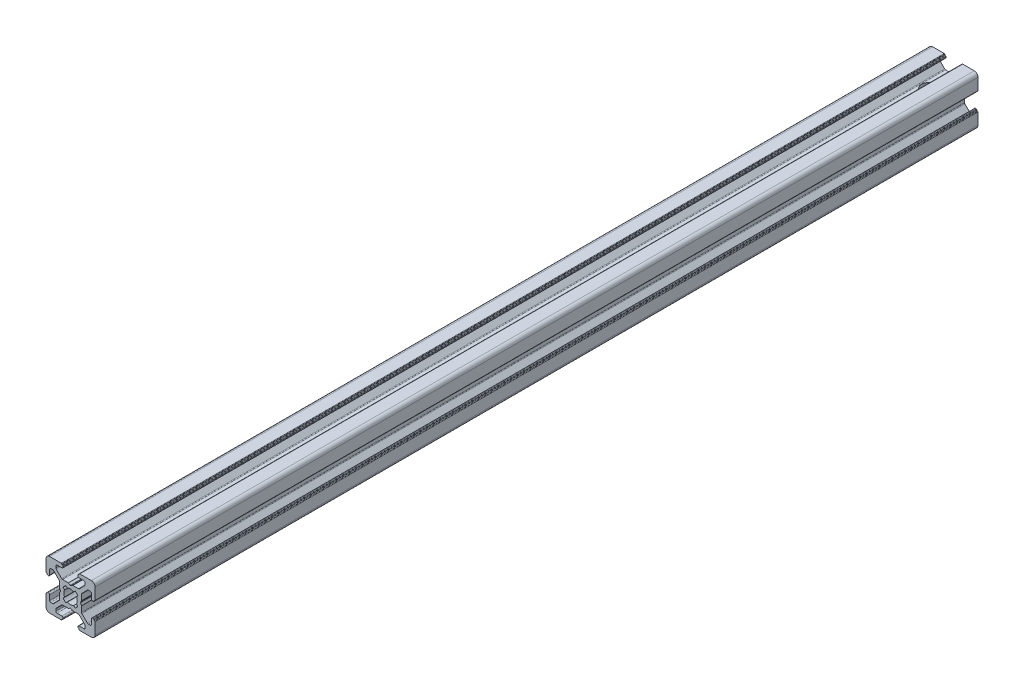
SolidWorks part; units mm, degrees
ref_plane "Ön Düzlem" through (0, 0, 0) normal (0, 0, 1) x (1, 0, 0)
ref_plane "Üst Düzlem" through (0, 0, 0) normal (0, 1, 0) x (1, 0, 0)
ref_plane "Sağ Düzlem" through (0, 0, 0) normal (1, 0, 0) x (0, 0, -1)
sketch "Çizim1" plane through (0, 0, 0) normal (0, 0, 1) x (1, 0, 0)
  line L0 (-2.9922, 1.9099) -> (-2.4453, 1.2582)
  line L1 (-2.4453, -1.2582) -> (-2.9922, -1.9099)
  line L2 (-1.9139, -2.9896) -> (-1.2582, -2.4453)
  line L3 (1.2582, -2.4453) -> (1.9139, -2.9896)
  line L4 (2.9922, -1.9099) -> (2.4453, -1.2582)
  line L5 (2.4453, 1.2582) -> (2.9922, 1.9099)
  line L6 (1.9139, 2.9896) -> (1.2582, 2.4453)
  line L7 (-1.2582, 2.4453) -> (-1.9139, 2.9896)
  line L8 (-3.75, 10) -> (-8.5, 10)
  line L9 (-3.55, 9.7) -> (-3.55, 9.8)
  line L10 (-3.2, 9.5) -> (-3.35, 9.5)
  line L11 (-3, 9) -> (-3, 9.3)
  line L12 (-5.5, 8.5) -> (-3.5, 8.5)
  line L13 (-6, 7.2678) -> (-6, 8)
  line L14 (-3.5858, 4.6464) -> (-5.8536, 6.9142)
  line L15 (-0.9536, 4.5) -> (-3.2322, 4.5)
  line L16 (-0.1, 4.0381) -> (-0.8536, 4.4732)
  line L17 (0.8536, 4.4732) -> (0.1, 4.0381)
  line L18 (3.2322, 4.5) -> (0.9536, 4.5)
  line L19 (5.8536, 6.9142) -> (3.5858, 4.6464)
  line L20 (6, 8) -> (6, 7.2678)
  line L21 (3.5, 8.5) -> (5.5, 8.5)
  line L22 (3, 9.3) -> (3, 9)
  line L23 (3.35, 9.5) -> (3.2, 9.5)
  line L24 (3.55, 9.8) -> (3.55, 9.7)
  line L25 (8.5, 10) -> (3.75, 10)
  line L26 (10, 3.75) -> (10, 8.5)
  line L27 (9.7, 3.55) -> (9.8, 3.55)
  line L28 (9.5, 3.2) -> (9.5, 3.35)
  line L29 (9, 3) -> (9.3, 3)
  line L30 (8.5, 5.5) -> (8.5, 3.5)
  line L31 (7.2678, 6) -> (8, 6)
  line L32 (4.6464, 3.5858) -> (6.9142, 5.8536)
  line L33 (4.5, 0.9536) -> (4.5, 3.2322)
  line L34 (4.0381, 0.1) -> (4.4732, 0.8536)
  line L35 (4.4732, -0.8536) -> (4.0381, -0.1)
  line L36 (4.5, -3.2322) -> (4.5, -0.9536)
  line L37 (6.9142, -5.8536) -> (4.6464, -3.5858)
  line L38 (8, -6) -> (7.2678, -6)
  line L39 (8.5, -3.5) -> (8.5, -5.5)
  line L40 (9.3, -3) -> (9, -3)
  line L41 (9.5, -3.35) -> (9.5, -3.2)
  line L42 (9.8, -3.55) -> (9.7, -3.55)
  line L43 (10, -8.5) -> (10, -3.75)
  line L44 (3.75, -10) -> (8.5, -10)
  line L45 (3.55, -9.7) -> (3.55, -9.8)
  line L46 (3.2, -9.5) -> (3.35, -9.5)
  line L47 (3, -9) -> (3, -9.3)
  line L48 (5.5, -8.5) -> (3.5, -8.5)
  line L49 (6, -7.2678) -> (6, -8)
  line L50 (3.5858, -4.6464) -> (5.8536, -6.9142)
  line L51 (0.9536, -4.5) -> (3.2322, -4.5)
  line L52 (0.1, -4.0381) -> (0.8536, -4.4732)
  line L53 (-0.8536, -4.4732) -> (-0.1, -4.0381)
  line L54 (-3.2322, -4.5) -> (-0.9536, -4.5)
  line L55 (-5.8536, -6.9142) -> (-3.5858, -4.6464)
  line L56 (-6, -8) -> (-6, -7.2678)
  line L57 (-3.5, -8.5) -> (-5.5, -8.5)
  line L58 (-3, -9.3) -> (-3, -9)
  line L59 (-3.35, -9.5) -> (-3.2, -9.5)
  line L60 (-3.55, -9.8) -> (-3.55, -9.7)
  line L61 (-8.5, -10) -> (-3.75, -10)
  line L62 (-10, -3.75) -> (-10, -8.5)
  line L63 (-9.7, -3.55) -> (-9.8, -3.55)
  line L64 (-9.5, -3.2) -> (-9.5, -3.35)
  line L65 (-9, -3) -> (-9.3, -3)
  line L66 (-8.5, -5.5) -> (-8.5, -3.5)
  line L67 (-7.2678, -6) -> (-8, -6)
  line L68 (-4.6464, -3.5858) -> (-6.9142, -5.8536)
  line L69 (-4.5, -0.9536) -> (-4.5, -3.2322)
  line L70 (-4.0381, -0.1) -> (-4.4732, -0.8536)
  line L71 (-4.4732, 0.8536) -> (-4.0381, 0.1)
  line L72 (-4.5, 3.2322) -> (-4.5, 0.9536)
  line L73 (-6.9142, 5.8536) -> (-4.6464, 3.5858)
  line L74 (-8, 6) -> (-7.2678, 6)
  line L75 (-8.5, 3.5) -> (-8.5, 5.5)
  line L76 (-9.3, 3) -> (-9, 3)
  line L77 (-9.5, 3.35) -> (-9.5, 3.2)
  line L78 (-9.8, 3.55) -> (-9.7, 3.55)
  line L79 (-10, 8.5) -> (-10, 3.75)
  arc A0 (-2.4453, 1.2582) -> (-2.4453, -1.2582) centre (0, 0) ccw
  arc A1 (-2.9922, -1.9099) -> (-1.9139, -2.9896) centre (0, 0) ccw
  arc A2 (-1.2582, -2.4453) -> (1.2582, -2.4453) centre (0, 0) ccw
  arc A3 (1.9139, -2.9896) -> (2.9922, -1.9099) centre (0, 0) ccw
  arc A4 (2.4453, -1.2582) -> (2.4453, 1.2582) centre (0, 0) ccw
  arc A5 (2.9922, 1.9099) -> (1.9139, 2.9896) centre (0, 0) ccw
  arc A6 (1.2582, 2.4453) -> (-1.2582, 2.4453) centre (0, 0) ccw
  arc A7 (-1.9139, 2.9896) -> (-2.9922, 1.9099) centre (0, 0) ccw
  arc A8 (-3.55, 9.8) -> (-3.75, 10) centre (-3.75, 9.8) ccw
  arc A9 (-3.55, 9.7) -> (-3.35, 9.5) centre (-3.35, 9.7) ccw
  arc A10 (-3, 9.3) -> (-3.2, 9.5) centre (-3.2, 9.3) ccw
  arc A11 (-3.5, 8.5) -> (-3, 9) centre (-3.5, 9) ccw
  arc A12 (-5.5, 8.5) -> (-6, 8) centre (-5.5, 8) ccw
  arc A13 (-6, 7.2678) -> (-5.8536, 6.9142) centre (-5.5, 7.2678) ccw
  arc A14 (-3.5858, 4.6464) -> (-3.2322, 4.5) centre (-3.2322, 5) ccw
  arc A15 (-0.8536, 4.4732) -> (-0.9536, 4.5) centre (-0.9536, 4.3) ccw
  arc A16 (-0.1, 4.0381) -> (0.1, 4.0381) centre (0, 4.2113) ccw
  arc A17 (0.9536, 4.5) -> (0.8536, 4.4732) centre (0.9536, 4.3) ccw
  arc A18 (3.2322, 4.5) -> (3.5858, 4.6464) centre (3.2322, 5) ccw
  arc A19 (5.8536, 6.9142) -> (6, 7.2678) centre (5.5, 7.2678) ccw
  arc A20 (6, 8) -> (5.5, 8.5) centre (5.5, 8) ccw
  arc A21 (3, 9) -> (3.5, 8.5) centre (3.5, 9) ccw
  arc A22 (3.2, 9.5) -> (3, 9.3) centre (3.2, 9.3) ccw
  arc A23 (3.35, 9.5) -> (3.55, 9.7) centre (3.35, 9.7) ccw
  arc A24 (3.75, 10) -> (3.55, 9.8) centre (3.75, 9.8) ccw
  arc A25 (10, 8.5) -> (8.5, 10) centre (8.5, 8.5) ccw
  arc A26 (9.8, 3.55) -> (10, 3.75) centre (9.8, 3.75) ccw
  arc A27 (9.7, 3.55) -> (9.5, 3.35) centre (9.7, 3.35) ccw
  arc A28 (9.3, 3) -> (9.5, 3.2) centre (9.3, 3.2) ccw
  arc A29 (8.5, 3.5) -> (9, 3) centre (9, 3.5) ccw
  arc A30 (8.5, 5.5) -> (8, 6) centre (8, 5.5) ccw
  arc A31 (7.2678, 6) -> (6.9142, 5.8536) centre (7.2678, 5.5) ccw
  arc A32 (4.6464, 3.5858) -> (4.5, 3.2322) centre (5, 3.2322) ccw
  arc A33 (4.4732, 0.8536) -> (4.5, 0.9536) centre (4.3, 0.9536) ccw
  arc A34 (4.0381, 0.1) -> (4.0381, -0.1) centre (4.2113, 0) ccw
  arc A35 (4.5, -0.9536) -> (4.4732, -0.8536) centre (4.3, -0.9536) ccw
  arc A36 (4.5, -3.2322) -> (4.6464, -3.5858) centre (5, -3.2322) ccw
  arc A37 (6.9142, -5.8536) -> (7.2678, -6) centre (7.2678, -5.5) ccw
  arc A38 (8, -6) -> (8.5, -5.5) centre (8, -5.5) ccw
  arc A39 (9, -3) -> (8.5, -3.5) centre (9, -3.5) ccw
  arc A40 (9.5, -3.2) -> (9.3, -3) centre (9.3, -3.2) ccw
  arc A41 (9.5, -3.35) -> (9.7, -3.55) centre (9.7, -3.35) ccw
  arc A42 (10, -3.75) -> (9.8, -3.55) centre (9.8, -3.75) ccw
  arc A43 (8.5, -10) -> (10, -8.5) centre (8.5, -8.5) ccw
  arc A44 (3.55, -9.8) -> (3.75, -10) centre (3.75, -9.8) ccw
  arc A45 (3.55, -9.7) -> (3.35, -9.5) centre (3.35, -9.7) ccw
  arc A46 (3, -9.3) -> (3.2, -9.5) centre (3.2, -9.3) ccw
  arc A47 (3.5, -8.5) -> (3, -9) centre (3.5, -9) ccw
  arc A48 (5.5, -8.5) -> (6, -8) centre (5.5, -8) ccw
  arc A49 (6, -7.2678) -> (5.8536, -6.9142) centre (5.5, -7.2678) ccw
  arc A50 (3.5858, -4.6464) -> (3.2322, -4.5) centre (3.2322, -5) ccw
  arc A51 (0.8536, -4.4732) -> (0.9536, -4.5) centre (0.9536, -4.3) ccw
  arc A52 (0.1, -4.0381) -> (-0.1, -4.0381) centre (0, -4.2113) ccw
  arc A53 (-0.9536, -4.5) -> (-0.8536, -4.4732) centre (-0.9536, -4.3) ccw
  arc A54 (-3.2322, -4.5) -> (-3.5858, -4.6464) centre (-3.2322, -5) ccw
  arc A55 (-5.8536, -6.9142) -> (-6, -7.2678) centre (-5.5, -7.2678) ccw
  arc A56 (-6, -8) -> (-5.5, -8.5) centre (-5.5, -8) ccw
  arc A57 (-3, -9) -> (-3.5, -8.5) centre (-3.5, -9) ccw
  arc A58 (-3.2, -9.5) -> (-3, -9.3) centre (-3.2, -9.3) ccw
  arc A59 (-3.35, -9.5) -> (-3.55, -9.7) centre (-3.35, -9.7) ccw
  arc A60 (-3.75, -10) -> (-3.55, -9.8) centre (-3.75, -9.8) ccw
  arc A61 (-10, -8.5) -> (-8.5, -10) centre (-8.5, -8.5) ccw
  arc A62 (-9.8, -3.55) -> (-10, -3.75) centre (-9.8, -3.75) ccw
  arc A63 (-9.7, -3.55) -> (-9.5, -3.35) centre (-9.7, -3.35) ccw
  arc A64 (-9.3, -3) -> (-9.5, -3.2) centre (-9.3, -3.2) ccw
  arc A65 (-8.5, -3.5) -> (-9, -3) centre (-9, -3.5) ccw
  arc A66 (-8.5, -5.5) -> (-8, -6) centre (-8, -5.5) ccw
  arc A67 (-7.2678, -6) -> (-6.9142, -5.8536) centre (-7.2678, -5.5) ccw
  arc A68 (-4.6464, -3.5858) -> (-4.5, -3.2322) centre (-5, -3.2322) ccw
  arc A69 (-4.4732, -0.8536) -> (-4.5, -0.9536) centre (-4.3, -0.9536) ccw
  arc A70 (-4.0381, -0.1) -> (-4.0381, 0.1) centre (-4.2113, 0) ccw
  arc A71 (-4.5, 0.9536) -> (-4.4732, 0.8536) centre (-4.3, 0.9536) ccw
  arc A72 (-4.5, 3.2322) -> (-4.6464, 3.5858) centre (-5, 3.2322) ccw
  arc A73 (-6.9142, 5.8536) -> (-7.2678, 6) centre (-7.2678, 5.5) ccw
  arc A74 (-8, 6) -> (-8.5, 5.5) centre (-8, 5.5) ccw
  arc A75 (-9, 3) -> (-8.5, 3.5) centre (-9, 3.5) ccw
  arc A76 (-9.5, 3.2) -> (-9.3, 3) centre (-9.3, 3.2) ccw
  arc A77 (-9.5, 3.35) -> (-9.7, 3.55) centre (-9.7, 3.35) ccw
  arc A78 (-10, 3.75) -> (-9.8, 3.55) centre (-9.8, 3.75) ccw
  arc A79 (-8.5, 10) -> (-10, 8.5) centre (-8.5, 8.5) ccw
extrude "Yükseklik-Ekstrüzyon1" add sketch "Çizim1" along normal mid plane 360
sketch "Çizim2" plane through (0, 10, 0) normal (0, 1, 0) x (1, 0, 0)
  line L0 (10, -180) -> (10, 180) construction
  circle A0 centre (0, 170) radius 3
  point P2 (-0.6535, 184.1417)
  point P5 (0, 172.2206)
  dimension "D1" = 6
  dimension "D2" = 10
  dimension "D3" = 10
extrude "Kes-Ekstrüzyon1" cut sketch "Çizim2" against normal blind 36
